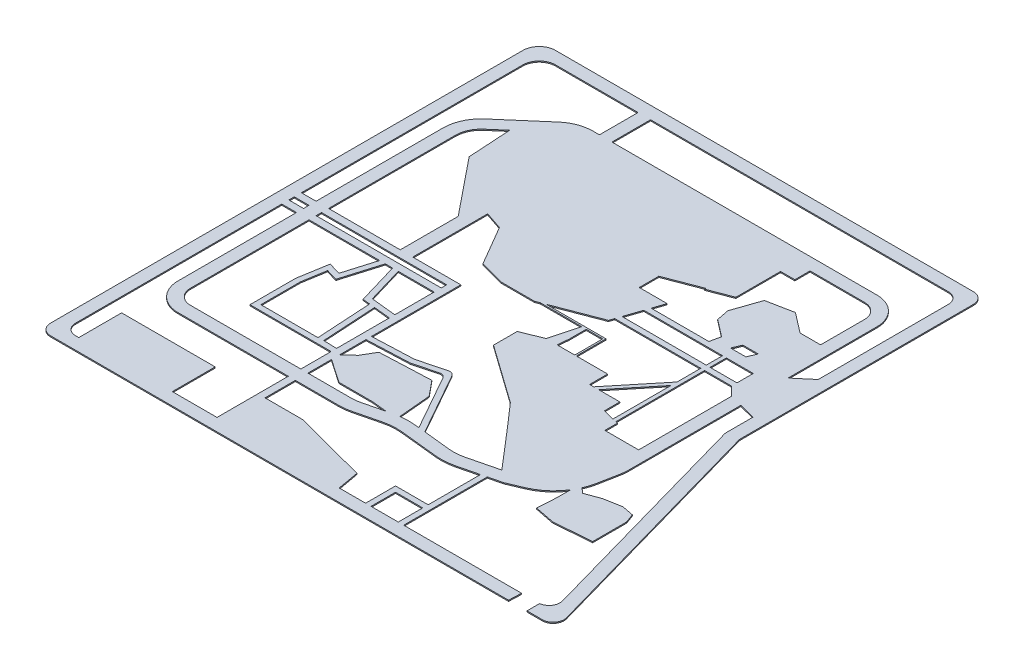
SolidWorks part; units mm, degrees
ref_plane "前视基准面" through (0, 0, 0) normal (0, 0, 1) x (1, 0, 0)
ref_plane "上视基准面" through (0, 0, 0) normal (0, 1, 0) x (1, 0, 0)
ref_plane "右视基准面" through (0, 0, 0) normal (1, 0, 0) x (0, 0, -1)
sketch "草图1" plane through (0, 0, 0) normal (0, 1, 0) x (1, 0, 0)
  line L0 (-409, 379) -> (-409, -489)
  line L1 (-389, -509) -> (452.6566, -509)
  line L2 (533.8277, -483.5708) -> (409.751, -43.6627)
  line L3 (409, -38.2335) -> (409, 389)
  line L4 (389, 409) -> (-379, 409)
  line L5 (366, 386) -> (-356, 386)
  line L6 (-386, 356) -> (-386, -466)
  line L7 (-366, -486) -> (453.5799, -486)
  line L8 (503.4431, -460.5708) -> (386.751, -46.8442)
  line L9 (386, -41.415) -> (386, 366)
  line L10 (409, 409) -> (-409, 409) construction
  line L11 (-409, 409) -> (-409, -509) construction
  line L12 (386, 386) -> (-386, 386) construction
  line L13 (-386, 386) -> (-386, -486) construction
  line L14 (-409, -509) -> (541, -509) construction
  line L15 (-386, -486) -> (510.6155, -486) construction
  line L16 (409, -41) -> (409, 409) construction
  line L17 (386, -44.1815) -> (386, 386) construction
  line L18 (541, -509) -> (409, -41) construction
  line L19 (510.6155, -486) -> (386, -44.1815) construction
  line L20 (486.5787, -485.8573) -> (486.5787, -509)
  line L21 (453.5799, -486) -> (452.6566, -509)
  line L22 (486.5787, -509) -> (514.5787, -509)
  arc A0 (-379, 409) -> (-409, 379) centre (-379, 379) ccw
  arc A1 (-356, 386) -> (-386, 356) centre (-356, 356) ccw
  arc A2 (-389, -509) -> (-409, -489) centre (-389, -489) cw
  arc A3 (-366, -486) -> (-386, -466) centre (-366, -466) cw
  arc A4 (389, 409) -> (409, 389) centre (389, 389) cw
  arc A5 (386, 366) -> (366, 386) centre (366, 366) ccw
  arc A6 (514.5787, -509) -> (533.8277, -483.5708) centre (514.5787, -489) ccw
  arc A7 (486.5787, -485.8573) -> (503.4431, -460.5708) centre (484.1941, -466) ccw
  arc A8 (409, -38.2335) -> (409.751, -43.6627) centre (429, -38.2335) ccw
  arc A9 (386.751, -46.8442) -> (386, -41.415) centre (406, -41.415) cw
  point P14 (-409, 409)
  dimension "D8" = 30
  dimension "D9" = 20
  dimension "D1" = 28
  dimension "D5" = 409
  dimension "D6" = 409
  dimension "D7" = 23
extrude "凸台-拉伸1" add sketch "草图1" along normal blind 2
sketch "草图5" plane through (0, 0, 0) normal (0, 1, 0) x (1, 0, 0)
  line L0 (-334.7588, 235.108) -> (-261.9829, 297.9729)
  line L1 (-216.2241, 315) -> (306, 315)
  line L2 (356, 265) -> (356, -189.4217)
  line L3 (354.1744, -208.4426) -> (347.7119, -241.7979)
  line L4 (288.4706, -314.8868) -> (261.2775, -326.3808)
  line L5 (261.2775, -326.3808) -> (190.4193, -343.8792)
  line L6 (156.0599, -346.255) -> (86.9685, -339.041)
  line L7 (52.609, -341.4168) -> (9.4153, -352.0835)
  line L8 (-14.5595, -355) -> (-309, -355)
  line L9 (-359, -305) -> (-359, 182.1351)
  line L10 (386, 366) -> (386, -41.415) construction
  line L11 (-356, 386) -> (366, 386) construction
  line L12 (-319.7238, 217.7026) -> (-246.9479, 280.5675)
  line L13 (-216.2241, 292) -> (306, 292)
  line L14 (333, 265) -> (333, -189.4217)
  line L15 (331.5943, -204.0678) -> (325.1318, -237.4231)
  line L16 (279.516, -293.7015) -> (253.9979, -304.4875)
  line L17 (253.9979, -304.4875) -> (184.9051, -321.55)
  line L18 (158.4483, -323.3793) -> (89.3569, -316.1654)
  line L19 (47.0948, -319.0876) -> (3.9011, -329.7543)
  line L20 (-14.5595, -332) -> (-309, -332)
  line L21 (-336, -305) -> (-336, 182.1351)
  arc A0 (-334.7588, 235.108) -> (-359, 182.1351) centre (-289, 182.1351) ccw
  arc A1 (-216.2241, 315) -> (-261.9829, 297.9729) centre (-216.2241, 245) ccw
  arc A2 (306, 315) -> (356, 265) centre (306, 265) cw
  arc A3 (86.9685, -339.041) -> (52.609, -341.4168) centre (76.5838, -438.5004) ccw
  arc A4 (-14.5595, -355) -> (9.4153, -352.0835) centre (-14.5595, -255) ccw
  arc A5 (156.0599, -346.255) -> (190.4193, -343.8792) centre (166.4446, -246.7956) ccw
  arc A6 (347.7119, -241.7979) -> (288.4706, -314.8868) centre (249.5375, -222.777) cw
  arc A7 (356, -189.4217) -> (354.1744, -208.4426) centre (256, -189.4217) cw
  arc A8 (-309, -355) -> (-359, -305) centre (-309, -305) cw
  arc A9 (-216.2241, 292) -> (-246.9479, 280.5675) centre (-216.2241, 245) ccw
  arc A10 (306, 292) -> (333, 265) centre (306, 265) cw
  arc A11 (333, -189.4217) -> (331.5943, -204.0678) centre (256, -189.4217) cw
  arc A12 (325.1318, -237.4231) -> (279.516, -293.7015) centre (249.5375, -222.777) cw
  arc A13 (158.4483, -323.3793) -> (184.9051, -321.55) centre (166.4446, -246.7956) ccw
  arc A14 (89.3569, -316.1654) -> (47.0948, -319.0876) centre (76.5838, -438.5004) ccw
  arc A15 (-14.5595, -332) -> (3.9011, -329.7543) centre (-14.5595, -255) ccw
  arc A16 (-309, -332) -> (-336, -305) centre (-309, -305) cw
  arc A17 (-319.7238, 217.7026) -> (-336, 182.1351) centre (-289, 182.1351) ccw
  point P30 (-161.7797, -355)
  dimension "D1" = 70
  dimension "D2" = 70
  dimension "D3" = 50
  dimension "D4" = 100
  dimension "D5" = 50
  dimension "D6" = 715
  dimension "D7" = 30
  dimension "D8" = 670
  dimension "D9" = 71
  dimension "D10" = 23
extrude "凸台-拉伸3" add sketch "草图5" along normal blind 2
sketch "草图4" plane through (0, 0, 0) normal (0, 1, 0) x (1, 0, 0)
  line L0 (-106, -486) -> (-106, -276.3275)
  line L1 (-366, -486) -> (453.5799, -486) construction
  line L2 (-106, -64) -> (-386, -64)
  line L3 (-386, 356) -> (-386, -466) construction
  line L5 (-93, -51) -> (-386, -51)
  line L6 (-106, -74) -> (-386, -74)
  line L7 (-106, -87) -> (-171.9333, -87)
  line L8 (-106, -74) -> (-106, -64)
  line L9 (-106, -486) -> (-106, -64) construction
  line L10 (-386, -51) -> (-386, -64)
  line L11 (-386, -74) -> (-386, -87)
  line L12 (-106, -486) -> (-93, -486)
  line L13 (-182.3566, -87) -> (-159.7543, -163.8671)
  line L14 (-159.7543, -163.8671) -> (-146.3073, -165.2462)
  line L15 (-206.2682, -87) -> (-223.3857, -144.6664)
  line L16 (-223.3857, -144.6664) -> (-246, -137.9537)
  line L17 (-246, -137.9537) -> (-255.1251, -192.5335)
  line L18 (-255.1251, -192.5335) -> (-255.1251, -276.3275)
  line L19 (-255.1251, -276.3275) -> (-106, -276.3275)
  line L20 (-171.9333, -87) -> (-152.0546, -154.6043)
  line L21 (-152.0546, -154.6043) -> (-106, -159.3274)
  line L22 (-195.8369, -87) -> (-216.6447, -157.0986)
  line L23 (-216.6447, -157.0986) -> (-238.0021, -150.759)
  line L24 (-238.0021, -150.759) -> (-245.1251, -193.3637)
  line L25 (-245.1251, -193.3637) -> (-245.1251, -266.3275)
  line L26 (-245.1251, -266.3275) -> (-140.2536, -266.3275)
  line L27 (-196.6816, -89.8456) -> (-216.6447, -157.0986) construction
  line L28 (-206.2682, -87) -> (-386, -87)
  line L29 (-106, -87) -> (-386, -87) construction
  line L30 (-182.3566, -87) -> (-195.8369, -87)
  line L31 (-172.7628, -84.179) -> (-152.0546, -154.6043) construction
  line L32 (-106, -159.3274) -> (-106, -87)
  line L33 (-152.0546, -154.6043) -> (-104.9798, -159.432) construction
  line L34 (-106, -266.3275) -> (-106, -169.3799)
  line L35 (-93, -410.76) -> (-23.5492, -410.76)
  line L36 (-23.5492, -410.76) -> (111.4917, -446.4503)
  line L39 (119.6786, -491.9989) -> (111.4917, -446.4503)
  line L40 (-93, -486) -> (119.6786, -491.9989)
  line L41 (-93, -410.76) -> (-93, -288.5702)
  line L42 (-93, -486) -> (-93, -51) construction
  line L43 (-93, -273.5437) -> (-74.9564, -257.3543)
  line L48 (-93, -215.2558) -> (-16.7213, -212.0109)
  line L49 (-16.7213, -212.0109) -> (32.3696, -199.1601)
  line L50 (43.6147, -203.926) -> (107.9366, -318.1053)
  line L51 (89.3569, -316.1654) -> (158.4483, -323.3793) construction
  line L52 (-93, -225.2649) -> (-15.2256, -221.9563)
  line L53 (-15.2256, -221.9563) -> (27.442, -210.787)
  line L54 (38.687, -215.5529) -> (99.224, -323.0135)
  line L55 (99.224, -323.0135) -> (107.9366, -318.1053)
  line L56 (39.8298, -197.2072) -> (107.9366, -318.1053) construction
  line L57 (-16.7213, -212.0109) -> (39.8298, -197.2072) construction
  line L58 (-15.2256, -221.9563) -> (34.9021, -208.8341) construction
  line L59 (34.9021, -208.8341) -> (99.224, -323.0135) construction
  line L60 (-92.575, -225.2468) -> (-15.2256, -221.9563) construction
  line L61 (-93, -215.2558) -> (-93, -51)
  line L62 (-93, -273.5437) -> (-93, -225.2649)
  line L63 (-74.9564, -257.3543) -> (-60.9233, -233.5817)
  line L64 (227, -486) -> (227, -441)
  line L65 (-146.3073, -165.2462) -> (-140.2536, -266.3275)
  line L66 (-136.2275, -166.2799) -> (-130.2715, -265.7297)
  line L67 (453.5799, -486) -> (-366, -486) construction
  line L68 (190.4193, -343.8792) -> (261.2775, -326.3808) construction
  line L69 (237, -486) -> (237, -326.4634)
  line L70 (237, -486) -> (237, -334.8456) construction
  line L71 (237, -326.4634) -> (227, -334.8456)
  line L72 (227, -486) -> (237, -486)
  line L73 (227, -431) -> (167, -431)
  line L74 (167, -431) -> (167, -486)
  line L75 (227, -441) -> (177, -441)
  line L76 (177, -441) -> (177, -486)
  line L77 (167, -486) -> (177, -486)
  line L78 (227, -431) -> (227, -334.8456)
  line L79 (227, -486) -> (227, -334.8456) construction
  line L80 (-136.3252, -164.6483) -> (-130.2715, -265.7297) construction
  line L81 (-136.2275, -166.2799) -> (-106, -169.3799)
  line L82 (-159.7543, -163.8671) -> (-106, -169.3799) construction
  line L83 (-245.1251, -266.3275) -> (-106, -266.3275) construction
  line L84 (-130.2715, -265.7297) -> (-106, -266.3275)
  line L85 (-60.9233, -233.5817) -> (32.3696, -229.6129)
  line L86 (32.3696, -229.6129) -> (55.1428, -257.3543)
  line L87 (55.1428, -257.3543) -> (61.1048, -323.0135)
  line L88 (61.1048, -323.0135) -> (12.0181, -318.1053)
  line L89 (12.0181, -318.1053) -> (-49.8554, -318.1053)
  line L90 (-49.8554, -318.1053) -> (-93, -288.5702)
  arc A0 (43.6147, -203.926) -> (32.3696, -199.1601) centre (34.9021, -208.8341) ccw
  arc A1 (27.442, -210.787) -> (38.687, -215.5529) centre (29.9744, -220.461) cw
  dimension "D13" = 10
  dimension "D2" = 280
  dimension "D3" = 435
  dimension "D5" = 10
  dimension "D9" = 10
  dimension "D14" = 320
  dimension "D15" = 10
  dimension "D16" = 55
  dimension "D17" = 60
  dimension "D1" = 13
  dimension "D4" = 13
  dimension "D6" = 10
  dimension "D7" = 10
  dimension "D12" = 10
  dimension "D18" = 10
extrude "凸台-拉伸2" add sketch "草图4" along normal blind 2
sketch "草图6" plane through (0, 0, 0) normal (0, 1, 0) x (1, 0, 0)
  line L0 (333.9793, -269.2014) -> (333.9793, -300.4079)
  line L1 (333.9793, -300.4079) -> (331.8328, -336.5432)
  line L2 (331.8328, -336.5432) -> (368.3342, -343.7407)
  line L3 (368.3342, -343.7407) -> (436.6594, -338.5237)
  line L4 (436.6594, -338.5237) -> (436.6594, -276.0938)
  line L5 (436.6594, -276.0938) -> (430.5204, -259.4059)
  line L6 (430.5204, -259.4059) -> (409.4554, -255.2522)
  line L7 (409.4554, -255.2522) -> (377.67, -260.9598)
  line L8 (377.67, -260.9598) -> (350.4405, -270.9767)
  line L19 (350.4405, -270.9767) -> (339.6427, -260.9598)
  line L20 (339.6427, -260.9598) -> (333.9793, -269.2014)
  line L22 (333, -150.3735) -> (271, -150.3735)
  line L23 (333, -189.4217) -> (333, 265) construction
  line L24 (271, -150.3735) -> (271, -127.4879)
  line L25 (271, -127.4879) -> (267.2694, -126.5313)
  line L26 (239.409, -119.3877) -> (239.409, -91.2417)
  line L27 (239.409, -91.2417) -> (200.4631, -91.2417)
  line L28 (183.8304, -91.2417) -> (183.8304, -58.1053)
  line L29 (183.8304, -58.1053) -> (126.3893, -58.1053)
  line L30 (70.9694, -58.1053) -> (33, -73.4211)
  line L31 (33, -73.4211) -> (33, -117.015)
  line L32 (33, -117.015) -> (91.1304, -158.2767)
  line L33 (91.1304, -158.2767) -> (139.9166, -192.9059)
  line L34 (139.9166, -192.9059) -> (177.2058, -235.577)
  line L35 (177.2058, -235.577) -> (239.409, -308.0902)
  line L36 (184.9051, -321.55) -> (253.9979, -304.4875) construction
  line L37 (333, -150.3735) -> (339.6427, -205.9171)
  line L38 (339.6427, -205.9171) -> (316.7224, -277.2151)
  line L39 (316.7224, -277.2151) -> (275.4857, -308.0902)
  line L40 (275.4857, -308.0902) -> (239.409, -308.0902)
  line L41 (-204.3424, -51) -> (-204.3424, 55.4994)
  line L42 (-93, -51) -> (-336, -51) construction
  line L43 (-356, 386) -> (366, 386) construction
  line L44 (-181.3424, -51) -> (-181.3424, 86.6344)
  line L45 (-204.3424, 386) -> (-181.3424, 386)
  line L46 (-204.3424, -51) -> (-181.3424, -51)
  line L47 (205.6821, 292) -> (205.6821, 264.023)
  line L48 (306, 292) -> (-216.2241, 292) construction
  line L49 (205.6821, 264.023) -> (179.4655, 264.023)
  line L50 (179.4655, 264.023) -> (179.4655, 181.9197)
  line L51 (179.4655, 181.9197) -> (137.594, 165.913)
  line L52 (137.594, 165.913) -> (138.3449, 168.7638)
  line L53 (138.3449, 168.7638) -> (75.1831, 144.6182)
  line L54 (75.1831, 144.6182) -> (75.1831, 108.6625)
  line L55 (75.1831, 108.6625) -> (126.3893, 108.6625)
  line L56 (126.3893, 108.6625) -> (118.9442, 86.6344)
  line L57 (99.1582, 28.0923) -> (16.3667, -3.5573)
  line L58 (0.7569, -9.5246) -> (-59.93, -9.5246)
  line L59 (-59.93, -9.5246) -> (-106.1434, 2.6478)
  line L60 (-106.1434, 2.6478) -> (-148.673, 75.5928)
  line L61 (-148.673, 75.5928) -> (-181.3424, 86.6344)
  line L62 (205.6821, 292) -> (-181.3424, 292)
  line L63 (-181.3424, 292) -> (-181.3424, 386)
  line L64 (-181.3424, -51) -> (-181.3424, 386) construction
  line L65 (225.0011, 86.6344) -> (118.9442, 86.6344)
  line L66 (386, 366) -> (386, -41.415) construction
  line L67 (316.7224, 46.6344) -> (267.2694, 46.6344)
  line L68 (316.7224, 76.6344) -> (267.2694, 76.6344)
  line L69 (316.7224, 36.6344) -> (267.2694, 36.6344)
  line L70 (386, 76.6344) -> (118.9442, 76.6344) construction
  line L71 (386, 36.6344) -> (105.4251, 36.6344) construction
  line L72 (115.5645, 76.6344) -> (105.4251, 46.6344)
  line L73 (102.0453, 36.6344) -> (99.1582, 28.0923)
  line L74 (386, 86.6344) -> (386, 76.6344)
  line L75 (386, 46.6344) -> (386, 36.6344)
  line L76 (386, 126.6135) -> (356, 101.2743)
  line L77 (356, -189.4217) -> (356, 265) construction
  line L78 (356, 101.2743) -> (333, 92.7016)
  line L79 (316.7224, 36.6344) -> (333, 20.3568)
  line L80 (333, 20.3568) -> (386, 6.9635)
  line L81 (386, 126.6135) -> (386, 6.9635)
  line L82 (316.7224, 76.6344) -> (316.7224, 46.6344)
  line L83 (386, 86.6344) -> (118.9442, 86.6344) construction
  line L84 (386, 46.6344) -> (105.4251, 46.6344) construction
  line L85 (333, 183.9763) -> (295.3025, 183.9763)
  line L86 (295.3025, 183.9763) -> (258.4794, 212.3018)
  line L87 (258.4794, 212.3018) -> (210.7218, 202.876)
  line L88 (210.7218, 202.876) -> (193.5677, 152.9754)
  line L89 (193.5677, 152.9754) -> (198.1447, 129.7853)
  line L90 (198.1447, 129.7853) -> (229.2147, 105.8853)
  line L91 (229.2147, 105.8853) -> (225.0011, 86.6344)
  line L92 (255.2504, 96.1558) -> (262.0809, 112.1934)
  line L93 (262.0809, 112.1934) -> (290.3786, 112.1934)
  line L94 (290.3786, 112.1934) -> (283.5481, 96.1558)
  line L95 (283.5481, 96.1558) -> (255.2504, 96.1558)
  line L96 (333, 183.9763) -> (333, 92.7016)
  line L97 (70.9694, -58.1053) -> (84.5469, -6.5573)
  line L98 (267.2694, 76.6344) -> (267.2694, 46.6344)
  line L99 (92.9061, -6.5573) -> (92.9061, -37.1987)
  line L100 (92.9061, -37.1987) -> (91.1304, -58.1053)
  line L101 (16.3667, -3.5573) -> (126.3893, -3.5573)
  line L102 (126.3893, -3.5573) -> (126.3893, -58.1053)
  line L103 (8.5191, -6.5573) -> (84.5469, -6.5573)
  line L104 (123.3893, -6.5573) -> (123.3893, -58.1053)
  line L105 (16.3667, -6.5573) -> (123.3893, -6.5573) construction
  line L106 (8.5191, -6.5573) -> (0.7569, -9.5246)
  line L107 (92.9061, -6.5573) -> (123.3893, -6.5573)
  line L109 (123.3893, -58.1053) -> (91.1304, -58.1053)
  line L110 (260.2694, -18.087) -> (200.4631, -91.2417)
  line L111 (260.2694, 76.6344) -> (260.2694, 46.6344)
  line L112 (260.2694, -7.0274) -> (191.4215, -91.2417)
  line L113 (262.1962, -4.6705) -> (195.0436, -86.8111) construction
  line L114 (267.6157, -9.1011) -> (200.4631, -91.2417) construction
  line L115 (260.2694, -18.087) -> (260.2694, -124.7365)
  line L116 (260.2694, 76.6344) -> (260.2694, -126.5313) construction
  line L117 (191.4215, -91.2417) -> (183.8304, -91.2417)
  line L118 (260.2694, -124.7365) -> (239.409, -119.3877)
  line L119 (260.2694, 36.6344) -> (102.0453, 36.6344)
  line L120 (260.2694, 46.6344) -> (105.4251, 46.6344)
  line L121 (267.2694, 36.6344) -> (267.2694, -126.5313)
  line L122 (267.2694, 76.6344) -> (267.2694, -126.5313) construction
  line L123 (260.2694, 36.6344) -> (260.2694, -7.0274)
  line L124 (260.2694, 76.6344) -> (115.5645, 76.6344)
  line L126 (-289.1639, 160.4211) -> (-294.0594, 239.8719)
  line L127 (-246.9479, 280.5675) -> (-319.7238, 217.7026) construction
  line L128 (-294.0594, 239.8719) -> (-246.7157, 292)
  line L129 (-246.7157, 292) -> (-204.3424, 292)
  line L130 (-204.3424, 292) -> (-204.3424, 386)
  line L131 (-204.3424, -51) -> (-204.3424, 386) construction
  line L132 (-289.1639, 160.4211) -> (-204.3424, 55.4994)
  spline S0 degree 3 poles (210.8683, 409) (269.5893, 365.9308) (222.9436, 277.171) (177.7826, 179.6779) (145.1568, 98.8718) (67.2239, -13.3337) (-119.0458, -12.4958) (-246.8793, 81.6707) (-319.2215, 202.4563) (-366.459, 275.006) (-409, 309) knots 0 0 0 0 0.163728 0.235377 0.313669 0.410964 0.603028 0.75488 0.84837 1 1 1 1 construction
  point P13 (352.6336, -329.0984)
  point P14 (377.6041, -343.0329)
  point P15 (331.8328, -336.5432)
  point P16 (333.9793, -300.4079)
  point P17 (377.67, -260.9598)
  point P18 (436.6594, -287.7349)
  point P19 (430.5204, -259.4059)
  point P20 (201.1508, 139.2805)
  point P21 (207.915, 194.7113)
  point P134 (0, 0)
  point P138 (196.0294, 160.1365)
  point P139 (198.1447, 129.7853)
  point P141 (258.4794, 212.3018)
  point P142 (-289.1639, 160.4211)
  point P143 (0, 0)
  point P144 (-210.397, 62.9887)
  point P145 (-181.3424, 86.6344)
  point P146 (165.5849, 202.876)
  point P147 (157.0986, 273.707)
  point P148 (151.0737, 210.8185)
  point P149 (145.2357, 197.157)
  point P150 (97.0445, 152.9754)
  point P151 (75.1831, 105.4342)
  point P152 (126.3893, 108.6625)
  point P153 (179.4655, 181.9197)
  point P156 (205.6821, 264.023)
  dimension "D2" = 10
  dimension "D3" = 62
  dimension "D4" = 300
  dimension "D5" = 260
  dimension "D9" = 50
  dimension "D6" = 23
  dimension "D7" = 10
  dimension "D8" = 10
  dimension "D10" = 3
  dimension "D11" = 7
  dimension "D12" = 7
extrude "凸台-拉伸4" add sketch "草图6" along normal blind 2
sketch "草图7" plane through (0, 0, 0) normal (0, 1, 0) x (1, 0, 0)
  line L1 (-360.0512, -407.289) -> (-188.09, -407.289)
  line L2 (-360.0512, -407.289) -> (-360.0512, -492.0458)
  line L4 (-188.09, -407.289) -> (-188.09, -492.0458)
  line L7 (-360.0512, -492.0458) -> (-188.09, -492.0458)
extrude "凸台-拉伸5" add sketch "草图7" along normal blind 2
